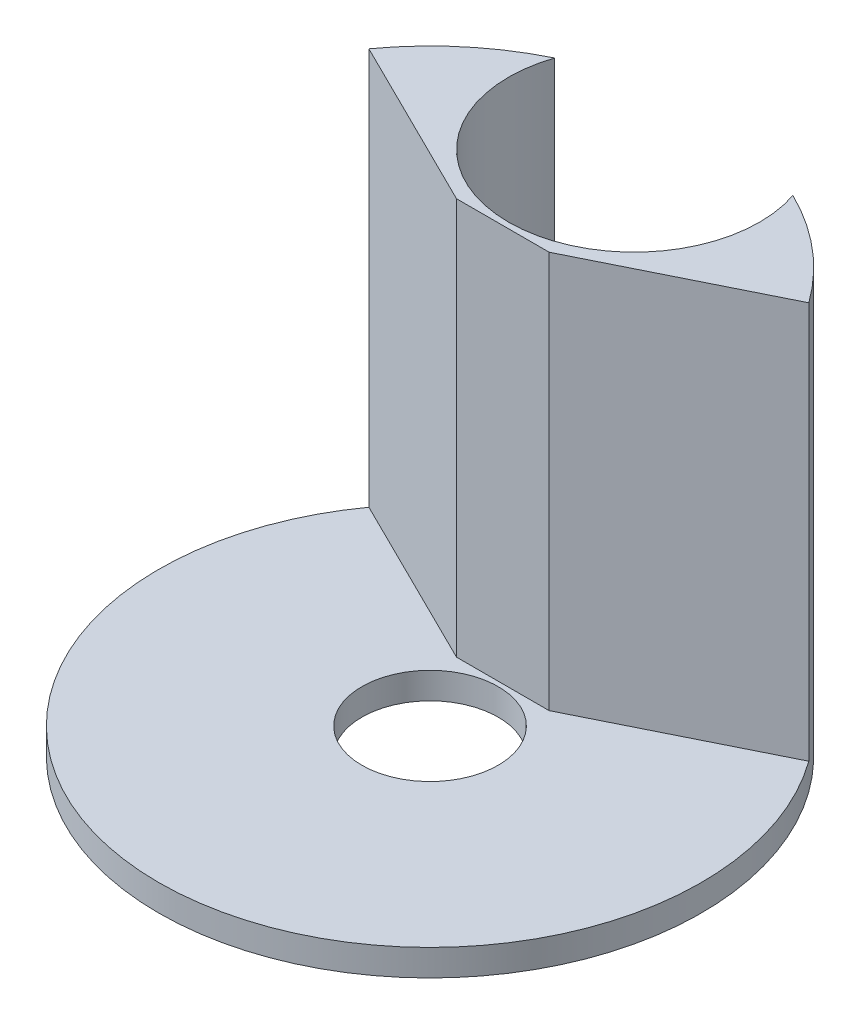
SolidWorks part; units mm, degrees
ref_plane "Front Plane" through (0, 0, 0) normal (0, 0, 1) x (1, 0, 0)
ref_plane "Top Plane" through (0, 0, 0) normal (0, 1, 0) x (1, 0, 0)
ref_plane "Right Plane" through (0, 0, 0) normal (1, 0, 0) x (0, 0, -1)
sketch "Sketch1" plane through (0, 0, 0) normal (0, 1, 0) x (1, 0, 0)
  circle A0 centre (0, 0) radius 20.5
  dimension "D1" = 41
extrude "Boss-Extrude1" add sketch "Sketch1" along normal blind 2
sketch "Sketch2" plane through (0, 2, 0) normal (0, 1, 0) x (1, 0, 0)
  circle A0 centre (0, 0) radius 5.15
  dimension "D1" = 10.3
extrude "Cut-Extrude1" cut sketch "Sketch2" against normal blind 3
sketch "Sketch3" plane through (0, 2, 0) normal (0, 1, 0) x (1, 0, 0)
  circle A0 centre (0, 13) radius 6.5
  dimension "D2" = 13
  dimension "D1" = 13
extrude "Cut-Extrude2" cut sketch "Sketch3" against normal blind 2
sketch "Sketch4" plane through (0, 2, 0) normal (0, 1, 0) x (1, 0, 0)
  line L0 (-3.5, 5.5) -> (-16.6208, 12)
  line L1 (3.5, 5.5) -> (16.6208, 12)
  line L4 (-3.5, 5.5) -> (3.5, 5.5)
  arc A0 (-16.6208, 12) -> (-9, 18.4187) centre (0, 0) cw
  circle A1 centre (0, 0) radius 20.5 construction
  arc A4 (9, 18.4187) -> (16.6208, 12) centre (0, 0) cw
  arc A6 (-9, 18.4187) -> (9, 18.4187) centre (0, 15.4184) ccw
  dimension "D1" = 12
  dimension "D2" = 12
  dimension "D3" = 5.5
  dimension "D4" = 5.5
  dimension "D5" = 3.5
  dimension "D6" = 3.5
  dimension "D7" = 9
  dimension "D8" = 9
extrude "Boss-Extrude4" add sketch "Sketch4" along normal blind 30
